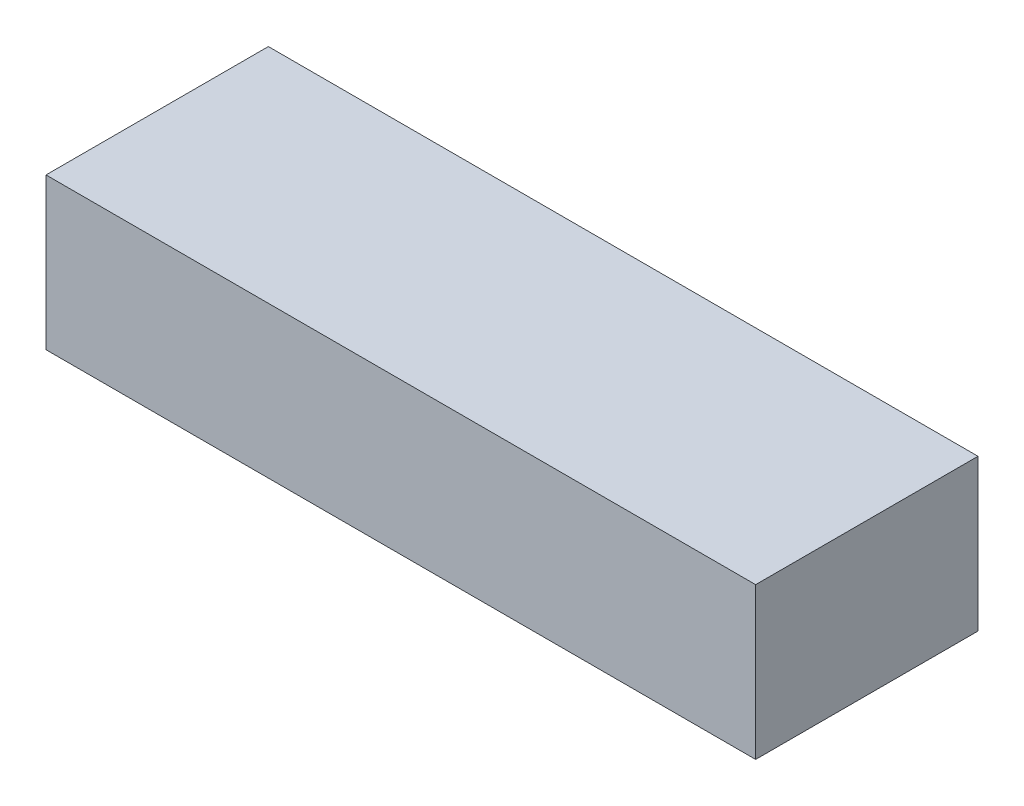
SolidWorks part; units mm, degrees
ref_plane "Front Plane" through (0, 0, 0) normal (0, 0, 1) x (1, 0, 0)
ref_plane "Top Plane" through (0, 0, 0) normal (0, 1, 0) x (1, 0, 0)
ref_plane "Right Plane" through (0, 0, 0) normal (1, 0, 0) x (0, 0, -1)
sketch "Sketch1" plane through (0, 0, 0) normal (0, 1, 0) x (1, 0, 0)
  line L1 (0, 0) -> (150, 0)
  line L2 (0, 0) -> (0, 47)
  line L3 (0, 47) -> (150, 47)
  line L4 (150, 0) -> (150, 47)
  dimension "D1" = 150
  dimension "D2" = 47
extrude "Boss-Extrude1" add sketch "Sketch1" along normal blind 32
